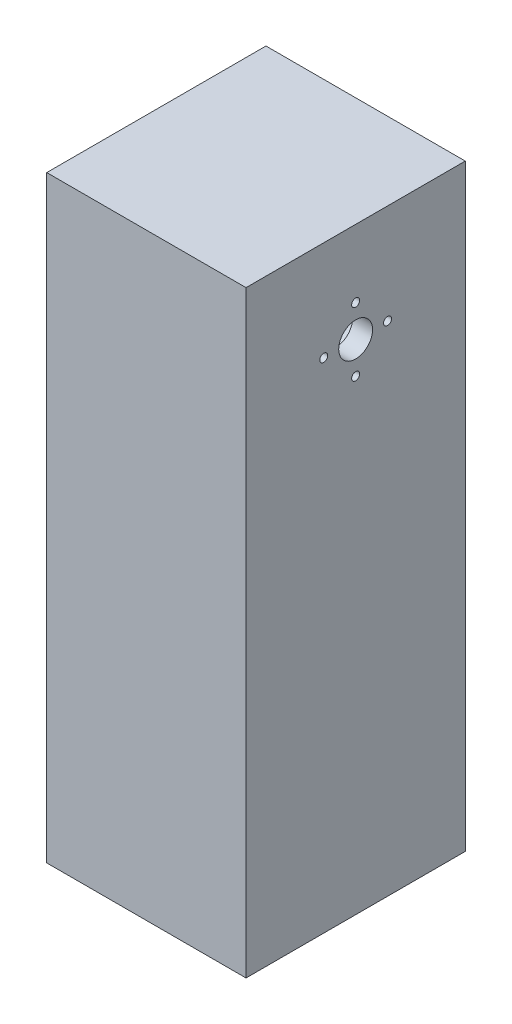
SolidWorks part; units mm, degrees
ref_plane "Front Plane" through (0, 0, 0) normal (0, 0, 1) x (1, 0, 0)
ref_plane "Top Plane" through (0, 0, 0) normal (0, 1, 0) x (1, 0, 0)
ref_plane "Right Plane" through (0, 0, 0) normal (1, 0, 0) x (0, 0, -1)
sketch "Sketch1" plane through (0, 0, 0) normal (0, 0, 1) x (1, 0, 0)
  line L1 (-25, 0) -> (25, 0)
  line L2 (-25, 0) -> (-25, -150)
  line L3 (-25, -150) -> (25, -150)
  line L4 (25, 0) -> (25, -150)
  dimension "D1" = 50
  dimension "D2" = 150
extrude "Boss-Extrude1" add sketch "Sketch1" against normal blind 55
sketch "Sketch2" plane through (25, 0, 0) normal (1, 0, 0) x (0, 0, -1)
  line L0 (55, 0) -> (0, 0) construction
  line L1 (0, -150) -> (0, 0) construction
  circle A0 centre (27.5, -25) radius 10.25
  dimension "D1" = 25
  dimension "D2" = 27.5
extrude "Cut-Extrude1" cut sketch "Sketch2" against normal blind 45 and the other way through all
sketch "Sketch7" plane through (-20, 0, 0) normal (1, 0, 0) x (0, 0, -1)
  line L0 (27.5, -17) -> (27.5, -33) construction
  circle A0 centre (27.5, -25) radius 8
  circle A1 centre (27.5, -17) radius 1
  circle A2 centre (35.5, -25) radius 1
  circle A3 centre (27.5, -33) radius 1
  circle A4 centre (19.5, -25) radius 1
  circle A5 centre (27.5, -25) radius 4.25
  point P14 (27.5, -25)
  dimension "D1" = 16
  dimension "D2" = 2
  dimension "D4" = 8.5
  dimension "D3" = 4
extrude "Cut-Extrude3" cut sketch "Sketch7" against normal blind 10 contours L0 A0 A1 | A0 A1 | A0 L0 A1 | A0 A4 | A0 A4 | L0 A3 A0 | A3 L0 A0 | A0 A3 | A0 A2 | A0 A2 | A5 L0 | L0 A5
sketch "Sketch8" plane through (-20, 0, 0) normal (1, 0, 0) x (0, 0, -1)
  circle A0 centre (27.5, -25) radius 10.25
  circle A1 centre (27.5, -17) radius 1
  circle A2 centre (27.5, -25) radius 4.25
  circle A3 centre (35.5, -25) radius 1
  circle A4 centre (27.5, -33) radius 1
  circle A5 centre (19.5, -25) radius 1
  point P16 (27.5, -25)
  dimension "D1" = 4
extrude "Boss-Extrude2" add sketch "Sketch8" along normal blind 45
sketch "Sketch9" plane through (-25, 0, 0) normal (-1, 0, 0) x (0, 0, 1)
  circle A0 centre (-27.5, -25) radius 10.25
extrude "Cut-Extrude4" cut sketch "Sketch9" against normal blind 45
